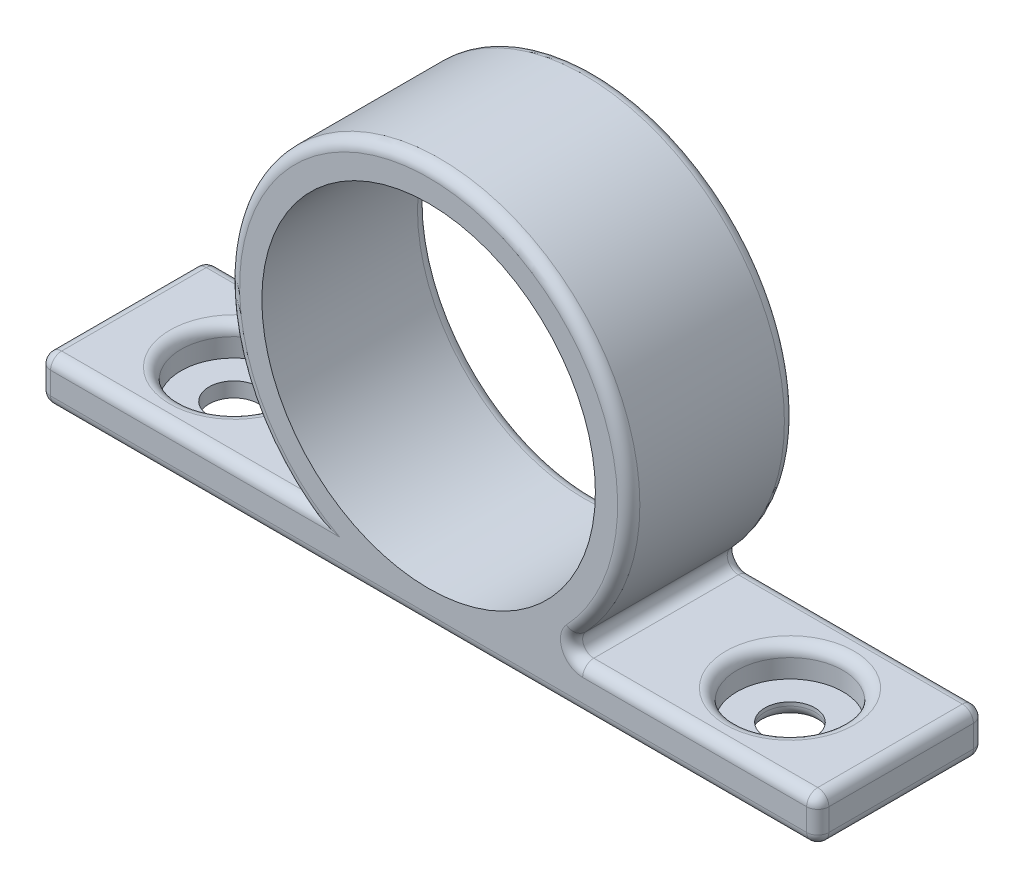
SolidWorks part; units mm, degrees
ref_plane "Front Plane" through (0, 0, 0) normal (0, 0, 1) x (1, 0, 0)
ref_plane "Top Plane" through (0, 0, 0) normal (0, 1, 0) x (1, 0, 0)
ref_plane "Right Plane" through (0, 0, 0) normal (1, 0, 0) x (0, 0, -1)
sketch "Sketch1" plane through (0, 0, 0) normal (0, 0, 1) x (1, 0, 0)
  line L4 (-35, 0) -> (-35, 4)
  line L5 (-35, 4) -> (-11.3137, 4)
  line L6 (0, 0) -> (0, 36) construction
  line L7 (35, 0) -> (-35, 0) construction
  line L8 (-35, 0) -> (35, 0)
  line L9 (35, 4) -> (11.3137, 4)
  line L10 (35, 4) -> (35, 0)
  line L11 (27, 4) -> (27, 0) construction
  arc A3 (-11.3137, 4) -> (11.3137, 4) centre (0, 18) cw
  circle A4 centre (0, 18) radius 15
  dimension "D1" = 30
  dimension "D3" = 18
  dimension "D6" = 18
  dimension "D2" = 8
  dimension "D4" = 4
  dimension "D5" = 27
extrude "Boss-Extrude1" add sketch "Sketch1" along normal mid plane 15
sketch "Sketch4" plane through (0, 4, 0) normal (0, 1, 0) x (1, 0, 0)
  line L0 (-25, 7.5) -> (-25, -7.5) construction
  line L1 (-11.3137, 7.5) -> (-35, 7.5) construction
  line L2 (-11.3137, -7.5) -> (-35, -7.5) construction
  line L3 (0, 7.5) -> (0, -7.5) construction
  line L4 (18, 7.5) -> (-18, 7.5) construction
  line L5 (-18, -7.5) -> (18, -7.5) construction
  point P6 (-25, 0)
  point P17 (25, 0)
  dimension "D1" = 25
hole_wizard "CBORE for #8 Binding Head Machine Screw1" positions "Sketch9" profile "Sketch10" counterbore size "#8" standard "ANSI Inch"
sketch "Sketch9" plane through (0, 4, 0) normal (0, 1, 0) x (1, 0, 0)
  point P0 (-25, 0)
  point P3 (25, 0)
sketch "Sketch10" plane through (-25, 4, 0) normal (1, 0, 0) x (0, 0, 1)
  line L0 (0, 0) -> (0, 11.3507)
  line L1 (0, 11.3507) -> (2.2479, 10)
  line L2 (2.2479, 10) -> (2.2479, 2.667)
  line L3 (2.2479, 2.667) -> (4.7625, 2.667)
  line L4 (4.7625, 2.667) -> (4.7625, 0)
  line L5 (4.7625, 0) -> (0, 0)
  line L10 (0, 11.3507) -> (-2.2479, 10) construction
  line L11 (0, -6.35) -> (0, 107.95) construction
  dimension "Hole Dia." = 4.4958
  dimension "Hole Depth" = 10
  dimension "C'Bore Dia." = 9.525
  dimension "C'Bore Depth" = 2.667
  dimension "Drill Angle" = 118
fillet "Fillet1" radius 1 21 edges at (-23.1569, 4, 7.5) (0, 36, 7.5) (23.1569, 4, 7.5) (0, 0, 7.5) (-35, 4, 0) (-35, 2, 7.5) (-35, 0, 0) (35, 0, 0) (35, 2, 7.5) (35, 4, 0) (15, 18, -7.5) (35, 2, -7.5) (23.1569, 4, -7.5) (0, 36, -7.5) (-23.1569, 4, -7.5) (-35, 2, -7.5) (0, 0, -7.5) (-25, 4, 4.7625) (25, 0, 2.2479) (11.3137, 4, 0) (25, 4, 4.7625)
